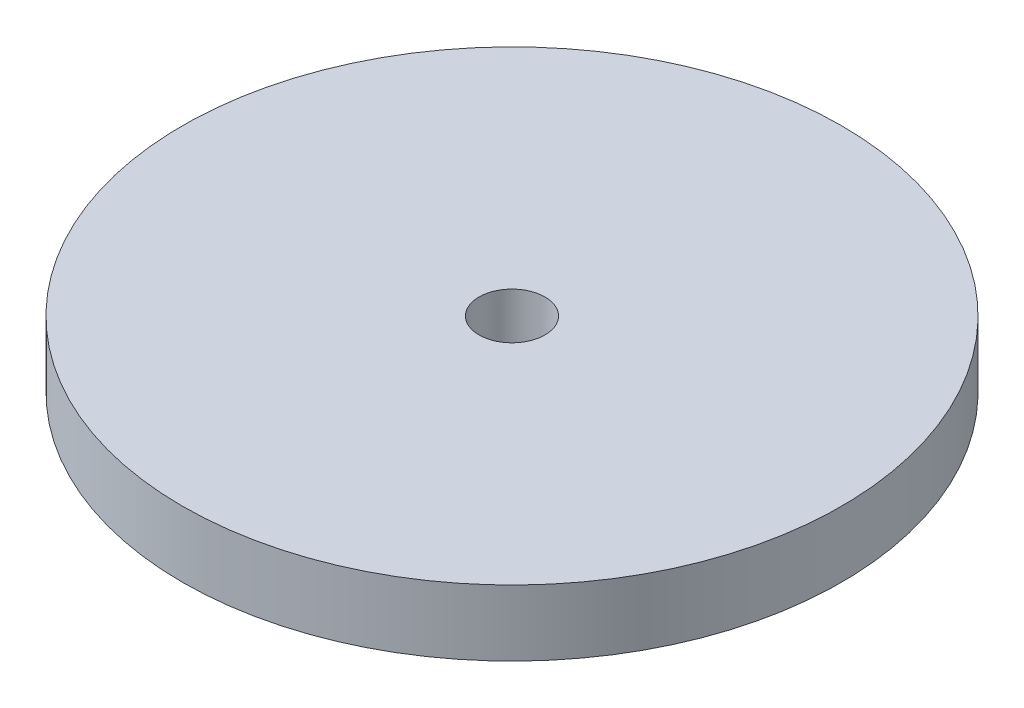
SolidWorks part; units mm, degrees
ref_plane "前视基准面" through (0, 0, 0) normal (0, 0, 1) x (1, 0, 0)
ref_plane "上视基准面" through (0, 0, 0) normal (0, 1, 0) x (1, 0, 0)
ref_plane "右视基准面" through (0, 0, 0) normal (1, 0, 0) x (0, 0, -1)
other "Configuration Table"
sketch "草图1" plane through (0, 0, 0) normal (0, 1, 0) x (1, 0, 0)
  circle A0 centre (0, 0) radius 20
  dimension "D1" = 40
extrude "凸台-拉伸1" add sketch "草图1" along normal blind 4
sketch "草图2" plane through (0, 0, 0) normal (0, -1, 0) x (1, 0, 0)
  circle A0 centre (0, 0) radius 2
extrude "切除-拉伸1" cut sketch "草图2" against normal through all and the other way through all
